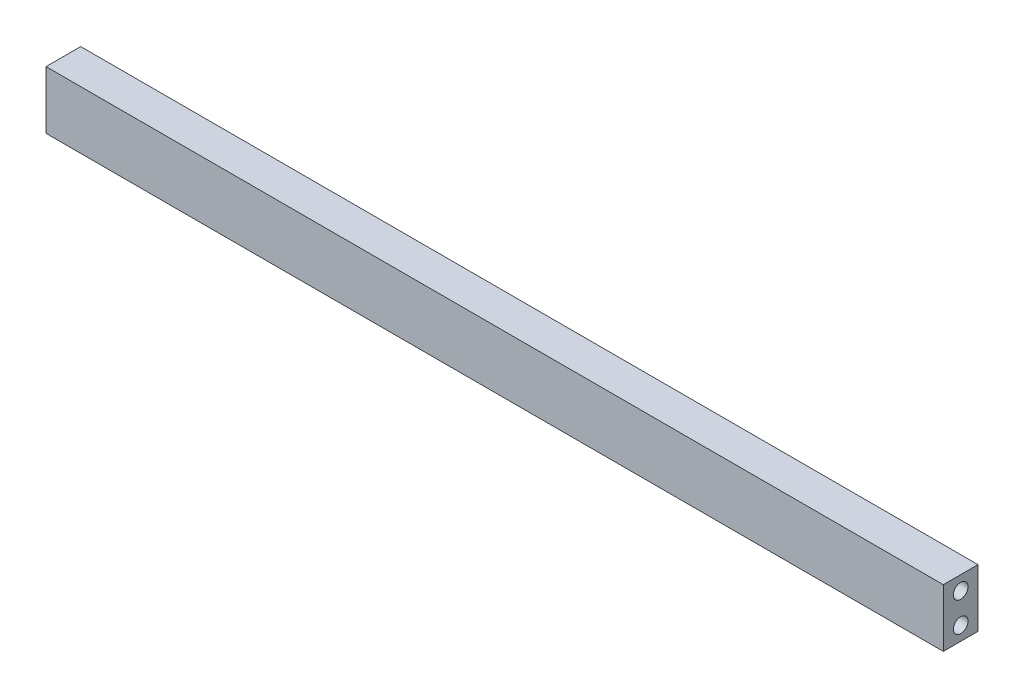
SolidWorks part; units mm, degrees
material "6061-T6 (SS)"
ref_plane "Front Plane" through (0, 0, 0) normal (0, 0, 1) x (1, 0, 0)
ref_plane "Top Plane" through (0, 0, 0) normal (0, 1, 0) x (1, 0, 0)
ref_plane "Right Plane" through (0, 0, 0) normal (1, 0, 0) x (0, 0, -1)
sketch "Sketch1" plane through (0, 0, 0) normal (1, 0, 0) x (0, 0, -1)
  line L1 (-4.7625, 7.9375) -> (4.7625, 7.9375)
  line L2 (-4.7625, 7.9375) -> (-4.7625, -7.9375)
  line L3 (-4.7625, -7.9375) -> (4.7625, -7.9375)
  line L4 (4.7625, 7.9375) -> (4.7625, -7.9375)
  line L5 (-4.7625, 7.9375) -> (4.7625, -7.9375) construction
  line L6 (-4.7625, -7.9375) -> (4.7625, 7.9375) construction
  point P0 (0, 0)
  dimension "D1" = 9.525
  dimension "D2" = 15.875
extrude "Boss-Extrude1" add sketch "Sketch1" along normal mid plane 246.38
sketch "Sketch2" plane through (123.19, 0, 0) normal (1, 0, 0) x (0, 0, -1)
  line L0 (0, 4.0894) -> (0, -4.0894) construction
  point P3 (0, 0)
  point P4 (0, 0)
  dimension "D1" = 8.1788
hole_wizard "Tap Drill for #10-32 Tap1" positions "Sketch3" profile "Sketch4" hole size "#10-32" standard "ANSI Inch"
sketch "Sketch3" plane through (123.19, 0, 0) normal (1, 0, 0) x (0, 0, -1)
  point P0 (0, 4.0894)
  point P3 (0, -4.0894)
sketch "Sketch4" plane through (123.19, 4.0894, 0) normal (0, 1, 0) x (0, 0, -1)
  line L0 (0, 0) -> (0, 11.3733)
  line L1 (0, 11.3733) -> (2.0193, 10.16)
  line L2 (2.0193, 10.16) -> (2.0193, 0)
  line L5 (2.0193, 0) -> (0, 0)
  line L10 (0, 11.3733) -> (-2.0193, 10.16) construction
  line L11 (0, -6.35) -> (0, 107.95) construction
  dimension "Hole Dia." = 4.0386
  dimension "Hole Depth" = 10.16
  dimension "Drill Angle" = 118
mirror "Mirror1" about plane through (0, 0, 0) normal (1, 0, 0) of "Tap Drill for #10-32 Tap1"
